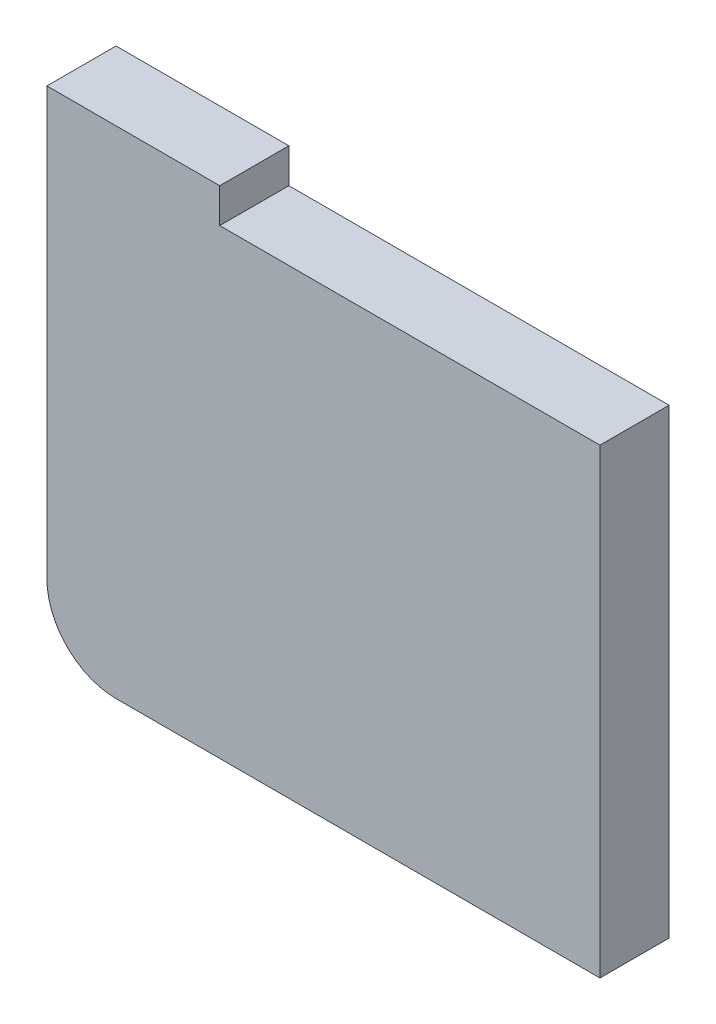
SolidWorks part; units mm, degrees
ref_plane "Front Plane" through (0, 0, 0) normal (0, 0, 1) x (1, 0, 0)
ref_plane "Top Plane" through (0, 0, 0) normal (0, 1, 0) x (1, 0, 0)
ref_plane "Right Plane" through (0, 0, 0) normal (1, 0, 0) x (0, 0, -1)
sketch "Sketch1" plane through (0, 0, 0) normal (0, 0, 1) x (1, 0, 0)
  line L0 (-37.8212, 0) -> (-37.8212, 0.2145) construction
  line L1 (-37.8212, 1) -> (-37.8212, 0.2145) construction
  line L2 (-37.8212, 0.5877) -> (-37.8212, 6) construction
  line L3 (-37.8212, 0) -> (-37.8212, -6) construction
  line L4 (-35.8212, -8) -> (15.1788, -8) construction
  line L7 (-37.8212, 0) -> (-37.8212, 0.2145)
  line L8 (-37.8212, 1) -> (-37.8212, 0.2145)
  line L9 (-37.8212, 0.5877) -> (-37.8212, 4)
  line L10 (-37.8212, 0) -> (-37.8212, -6)
  line L11 (-35.8212, -8) -> (-21.8212, -8)
  line L12 (-21.8212, 5.35) -> (-21.8212, -8)
  line L13 (-32.8212, 5.35) -> (-21.8212, 5.35)
  line L15 (-37.8212, 6.35) -> (-32.8212, 6.35)
  line L16 (-37.8212, 6.35) -> (-37.8212, 4)
  line L18 (-32.8212, 6.35) -> (-32.8212, 5.35)
  line L20 (-35.8212, -8) -> (15.1788, -8) construction
  line L22 (-36.8212, 6.35) -> (-38.8212, 6.35) construction
  arc A0 (-37.8212, -6) -> (-35.8212, -8) centre (-35.8212, -6) ccw construction
  arc A1 (-37.8212, -6) -> (-35.8212, -8) centre (-35.8212, -6) ccw
  point P10 (0, 0)
  point P15 (-22.8212, -8)
  point P18 (0, 0)
  point P19 (-22.8212, -8)
  point P20 (-21.7832, -8)
  point P23 (0, 0)
  point P24 (-21.7832, 4)
  point P25 (-21.873, 4.7493)
  point P26 (-37.8212, 4.818)
  point P27 (-37.8212, 6.35)
  point P30 (-21.8212, 5.4144)
  dimension "D1" = 5
  dimension "D2" = 11
  dimension "D3" = 1
extrude "Boss-Extrude1" add sketch "Sketch1" along normal blind 2 contours L10 A1 L11 L12 L13 L9 L8 L7
